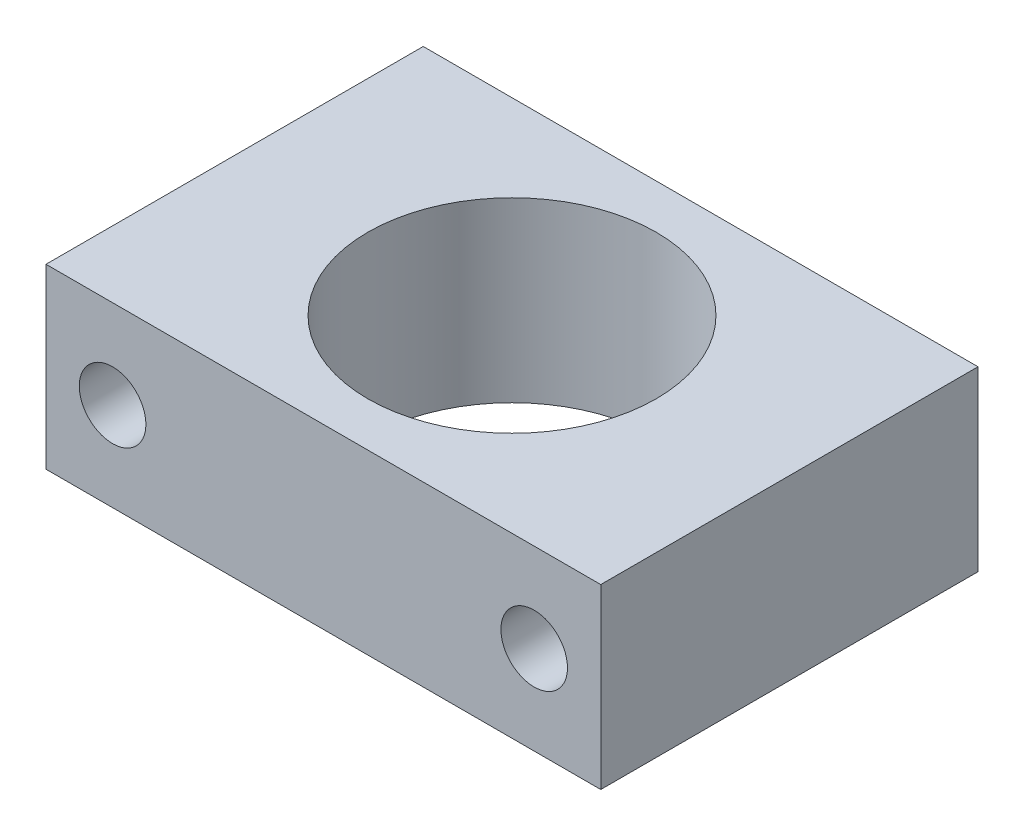
SolidWorks part; units mm, degrees
material "POM 乙缩醛共聚物"
ref_plane "前视基准面" through (0, 0, 0) normal (0, 0, 1) x (1, 0, 0)
ref_plane "上视基准面" through (0, 0, 0) normal (0, 1, 0) x (1, 0, 0)
ref_plane "右视基准面" through (0, 0, 0) normal (1, 0, 0) x (0, 0, -1)
sketch "草图1" plane through (0, 0, 0) normal (0, 1, 0) x (1, 0, 0)
  line L0 (0, 11.5657) -> (0, -7.1804) construction
  line L1 (-12.5, 8.5) -> (12.5, 8.5)
  line L2 (-12.5, 8.5) -> (-12.5, -8.5)
  line L3 (-12.5, -8.5) -> (12.5, -8.5)
  line L4 (12.5, 8.5) -> (12.5, -8.5)
  line L5 (-12.5, 8.5) -> (12.5, -8.5) construction
  line L6 (-12.5, -8.5) -> (12.5, 8.5) construction
  circle A1 centre (0, 0) radius 6.5
  dimension "D1" = 13
  dimension "D2" = 25
  dimension "D3" = 17
  dimension "D4" = 8.5
extrude "凸台-拉伸1" add sketch "草图1" along normal mid plane 8
sketch "草图2" plane through (0, 0, -8.5) normal (0, 0, -1) x (-1, 0, 0)
  line L0 (12.5, 0) -> (-12.5, 0) construction
  line L1 (12.5, 4) -> (12.5, -4) construction
  line L2 (-12.5, 4) -> (-12.5, -4) construction
  line L3 (0, -11.5013) -> (0, 14.7226) construction
  circle A0 centre (9.5, 0) radius 1.5
  circle A1 centre (-9.5, 0) radius 1.5
  dimension "D1" = 3
  dimension "D2" = 19
extrude "切除-拉伸1" cut sketch "草图2" against normal through all
